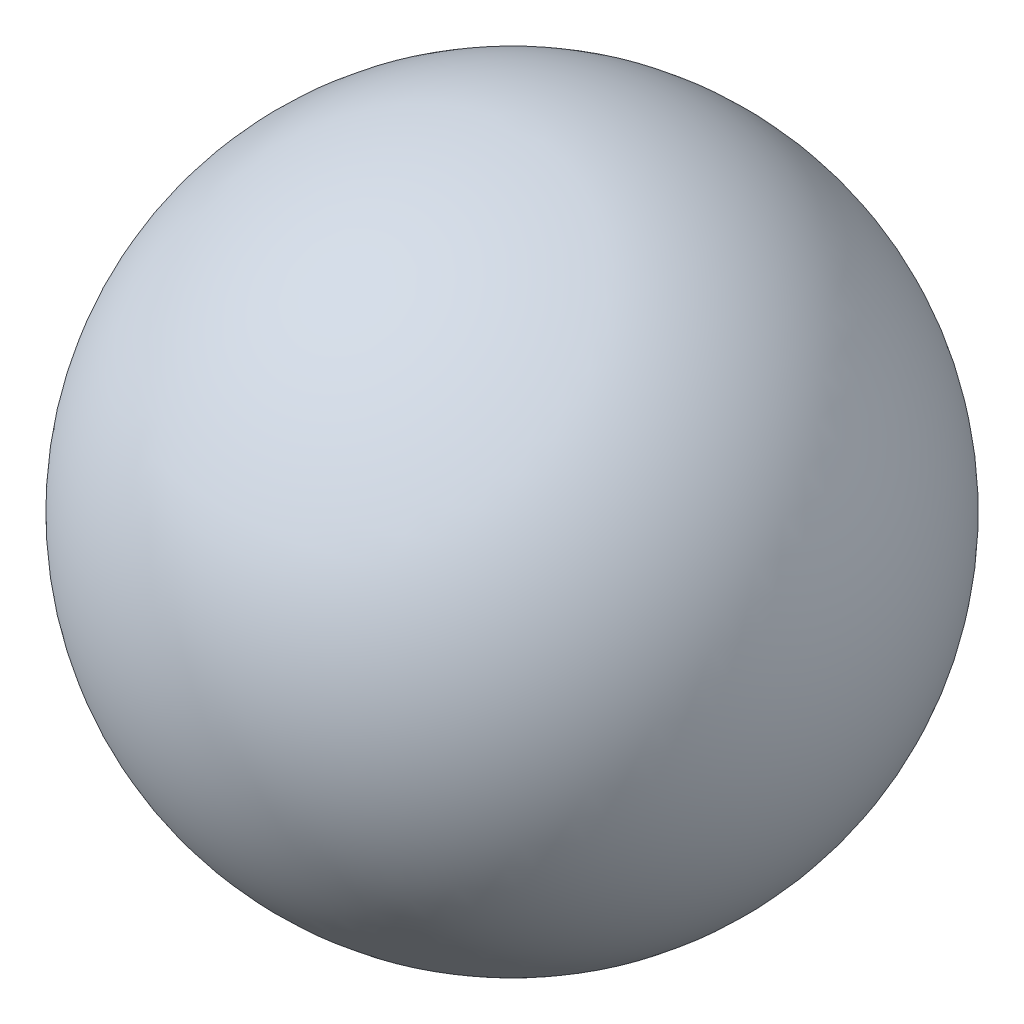
SolidWorks part; units mm, degrees
ref_plane "Plan de face" through (0, 0, 0) normal (0, 0, 1) x (1, 0, 0)
ref_plane "Plan de dessus" through (0, 0, 0) normal (0, 1, 0) x (1, 0, 0)
ref_plane "Plan de droite" through (0, 0, 0) normal (1, 0, 0) x (0, 0, -1)
sketch "Esquisse1" plane through (0, 0, 0) normal (1, 0, 0) x (0, 0, -1)
  line L0 (0, -4.8) -> (0, 4.8)
  arc A0 (0, 4.8) -> (0, -4.8) centre (0, 0) ccw
  point P4 (0, 0)
  dimension "D1" = 9.6
revolve "Révolution1" add sketch "Esquisse1" angle 360 about L0
scale "Echelle1" scale about centroid uniform scaling yes scale factor 0.69
